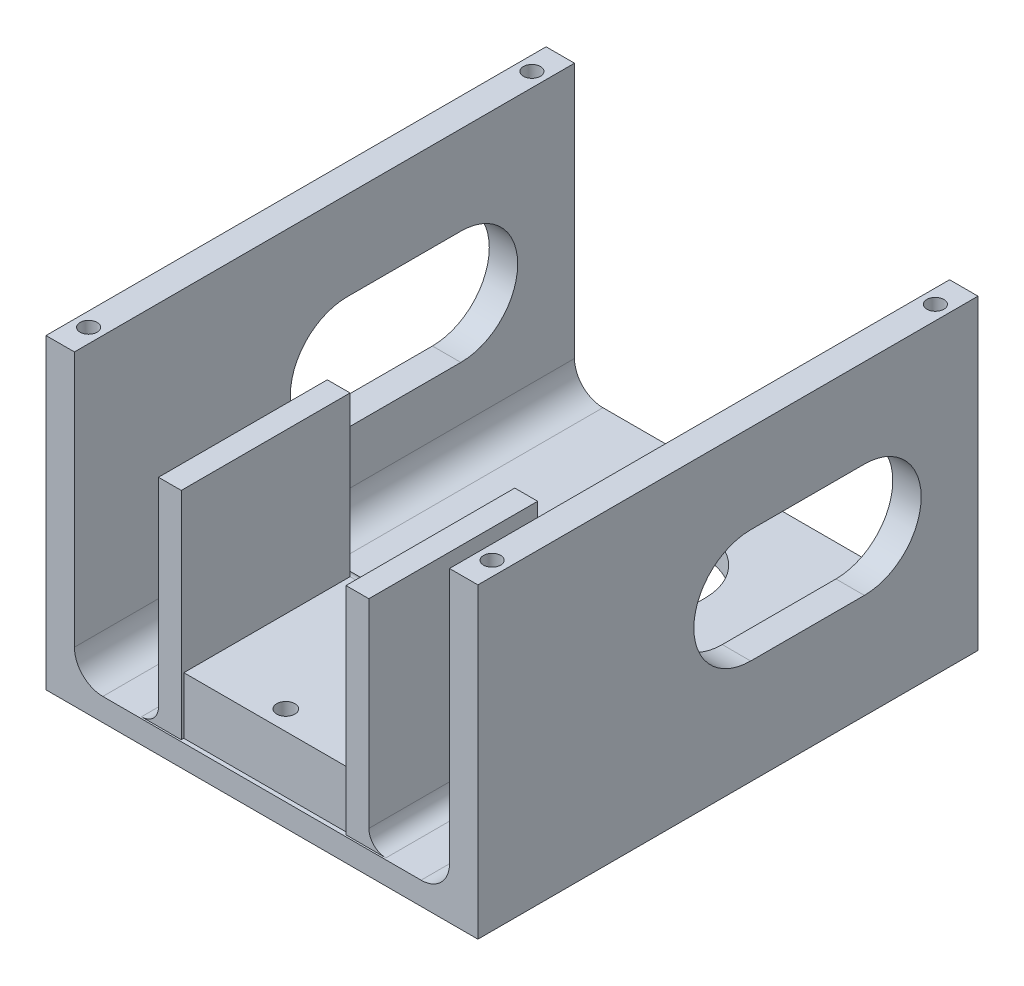
SolidWorks part; units mm, degrees
ref_plane "前视基准面" through (0, 0, 0) normal (0, 0, 1) x (1, 0, 0)
ref_plane "上视基准面" through (0, 0, 0) normal (0, 1, 0) x (1, 0, 0)
ref_plane "右视基准面" through (0, 0, 0) normal (1, 0, 0) x (0, 0, -1)
sketch "草图4" plane through (0, -14.4, 0) normal (0, -1, 0) x (1, 0, 0)
  circle A0 centre (-10, 2.1) radius 1.55
  circle A1 centre (10, 2.1) radius 1.55
sketch "草图5" plane through (0, -14.4, 0) normal (0, -1, 0) x (1, 0, 0)
  circle A0 centre (0, 25.8) radius 1.55
sketch "草图6" plane through (0, -14.4, 0) normal (0, -1, 0) x (1, 0, 0)
  line L0 (-14.4921, 29.7026) -> (-14.4988, 28.8) construction
  line L1 (-14.4954, 29.2513) -> (14.4974, 29.2513)
  line L2 (-14.4954, 29.2513) -> (-14.4954, 0.3)
  line L3 (-14.4954, 0.3) -> (14.4974, 0.3)
  line L4 (14.4974, 29.2513) -> (14.4974, 0.3)
extrude "凸台-拉伸2" add sketch "草图6" along normal blind 10
sketch "草图8" plane through (0, -24.4, 0) normal (0, -1, 0) x (1, 0, 0)
  line L6 (-38, 30) -> (38, 30)
  line L7 (-38, 30) -> (-38, -58)
  line L8 (-38, -58) -> (38, -58)
  line L9 (38, 30) -> (38, -58)
extrude "凸台-拉伸3" add sketch "草图8" along normal blind 4
extrude "切除-拉伸2" cut sketch "草图4" along normal blind 15
extrude "切除-拉伸3" cut sketch "草图5" along normal blind 15
sketch "草图10" plane through (0, -24.4, 0) normal (0, 1, 0) x (1, 0, 0)
  line L1 (14.4921, -29.7026) -> (18.5147, -29.7026)
  line L2 (14.4921, -29.7026) -> (14.4921, 0)
  line L3 (14.4921, 0) -> (18.5147, 0)
  line L4 (18.5147, -29.7026) -> (18.5147, 0)
extrude "凸台-拉伸9" add sketch "草图10" along normal blind 38
sketch "草图11" plane through (0, -24.4, 0) normal (0, 1, 0) x (1, 0, 0)
  line L1 (-14.4921, -29.7026) -> (-18.5023, -29.7026)
  line L2 (-14.4921, -29.7026) -> (-14.4921, 0)
  line L3 (-14.4921, 0) -> (-18.5023, 0)
  line L4 (-18.5023, -29.7026) -> (-18.5023, 0)
extrude "凸台-拉伸10" add sketch "草图11" along normal blind 38
sketch "草图14" plane through (0, -24.4, 0) normal (0, 1, 0) x (1, 0, 0)
  line L1 (-38, 58) -> (-33, 58)
  line L2 (-38, 58) -> (-38, -30)
  line L3 (-38, -30) -> (-33, -30)
  line L4 (-33, 58) -> (-33, -30)
  line L5 (38, -30) -> (-38, -30) construction
  dimension "D1" = 88
  dimension "D2" = 5
extrude "凸台-拉伸14" add sketch "草图14" along normal blind 50
sketch "草图15" plane through (0, -24.4, 0) normal (0, 1, 0) x (1, 0, 0)
  line L1 (38, 58) -> (33, 58)
  line L2 (38, 58) -> (38, -30)
  line L3 (38, -30) -> (33, -30)
  line L4 (33, 58) -> (33, -30)
  line L5 (38, -30) -> (-33, -30) construction
  dimension "D1" = 88
  dimension "D2" = 5
extrude "凸台-拉伸15" add sketch "草图15" along normal blind 50
sketch "草图19" plane through (0, -28.4, 0) normal (0, -1, 0) x (1, 0, 0)
  circle A2 centre (0, 25.8) radius 3.1
  circle A3 centre (-10, 2.1) radius 3.1
  circle A5 centre (10, 2.1) radius 3.1
  dimension "D1" = 6.2
  dimension "D2" = 6.2
  dimension "D3" = 6.2
sketch "草图21" plane through (0, 25.6, 0) normal (0, 1, 0) x (1, 0, 0)
  circle A0 centre (-35.5, 53) radius 1.4
  circle A1 centre (-35.5, -25) radius 1.4
  circle A2 centre (35.5, 53) radius 1.4
  circle A3 centre (35.5, -25) radius 1.4
extrude "切除-拉伸8" cut sketch "草图21" against normal blind 8
sketch "草图22" plane through (-38, 0, 0) normal (-1, 0, 0) x (0, 0, 1)
  line L3 (-38, 0) -> (-18, 0) construction
  line L5 (-38, 10) -> (-18, 10)
  line L6 (-38, -10) -> (-18, -10)
  arc A0 (-38, 10) -> (-38, -10) centre (-38, 0) ccw
  arc A1 (-18, -10) -> (-18, 10) centre (-18, 0) ccw
  point P9 (-28, 0)
extrude "切除-拉伸9" cut sketch "草图22" against normal blind 80
sketch "草图23" plane through (0, -24.4, 0) normal (0, 1, 0) x (1, 0, 0)
  line L4 (0, 38) -> (0, 18) construction
  line L6 (10, 38) -> (10, 18)
  line L7 (-10, 38) -> (-10, 18)
  arc A0 (10, 38) -> (-10, 38) centre (0, 38) ccw
  arc A1 (-10, 18) -> (10, 18) centre (0, 18) ccw
  point P10 (0, 28)
extrude "切除-拉伸11" cut sketch "草图23" against normal blind 80
fillet "圆角1" radius 5 1 edges at (-33, -24.4, -14)
fillet "圆角2" radius 5 1 edges at (33, -24.4, -14)
sketch "草图24" plane through (0, -24.4, 0) normal (0, 1, 0) x (1, 0, 0)
  line L1 (-14.4921, -0.3) -> (14.4921, -0.3)
  line L6 (-14.4921, -0.3) -> (-14.4921, 0)
  line L7 (-14.4921, 0) -> (14.4921, 0)
  line L8 (14.4921, -0.3) -> (14.4921, 0)
extrude "凸台-拉伸16" add sketch "草图24" along normal blind 10
sketch "草图25" plane through (0, -24.4, 0) normal (0, 1, 0) x (1, 0, 0)
  line L1 (-18.5023, 0) -> (18.5147, 0)
  line L2 (-18.5023, 0) -> (-18.5023, 2)
  line L3 (-18.5023, 2) -> (18.5147, 2)
  line L4 (18.5147, 0) -> (18.5147, 2)
  dimension "D1" = 2
extrude "凸台-拉伸18" add sketch "草图25" along normal blind 10
fillet "圆角7" radius 2 3 edges at (-18.5023, -14.4, -1) (18.5147, -14.4, -1) (0.0062, -14.4, -2)
fillet "圆角8" radius 3 1 edges at (18.5147, -24.4, 13.8513)
fillet "圆角9" radius 3 2 edges at (1.5062, -24.4, -2) (19.3934, -23.5213, -2)
fillet "圆角10" radius 3 2 edges at (-18.5023, -23.5213, -2.8787) (-18.5023, -24.4, 12.3513)
extrude "切除-拉伸12" cut sketch "草图19" against normal blind 3
sketch "草图27" plane through (0, 25.6, 0) normal (0, 1, 0) x (1, 0, 0)
  circle A0 centre (35.5, 53) radius 1.5
  circle A1 centre (-35.5, 53) radius 1.5
  circle A2 centre (-35.5, -25) radius 1.5
  circle A3 centre (35.5, -25) radius 1.5
  dimension "D1" = 3
  dimension "D2" = 3
  dimension "D3" = 3
  dimension "D4" = 3
extrude "切除-拉伸13" cut sketch "草图27" against normal blind 10
sketch "草图28" plane through (0, -28.4, 0) normal (0, -1, 0) x (1, 0, 0)
  circle A0 centre (-10, 2.1) radius 1.6
  circle A1 centre (10, 2.1) radius 1.6
  circle A2 centre (0, 25.8) radius 1.6
  dimension "D1" = 3.2
  dimension "D2" = 3.2
  dimension "D3" = 3.2
extrude "切除-拉伸15" cut sketch "草图28" against normal blind 15
